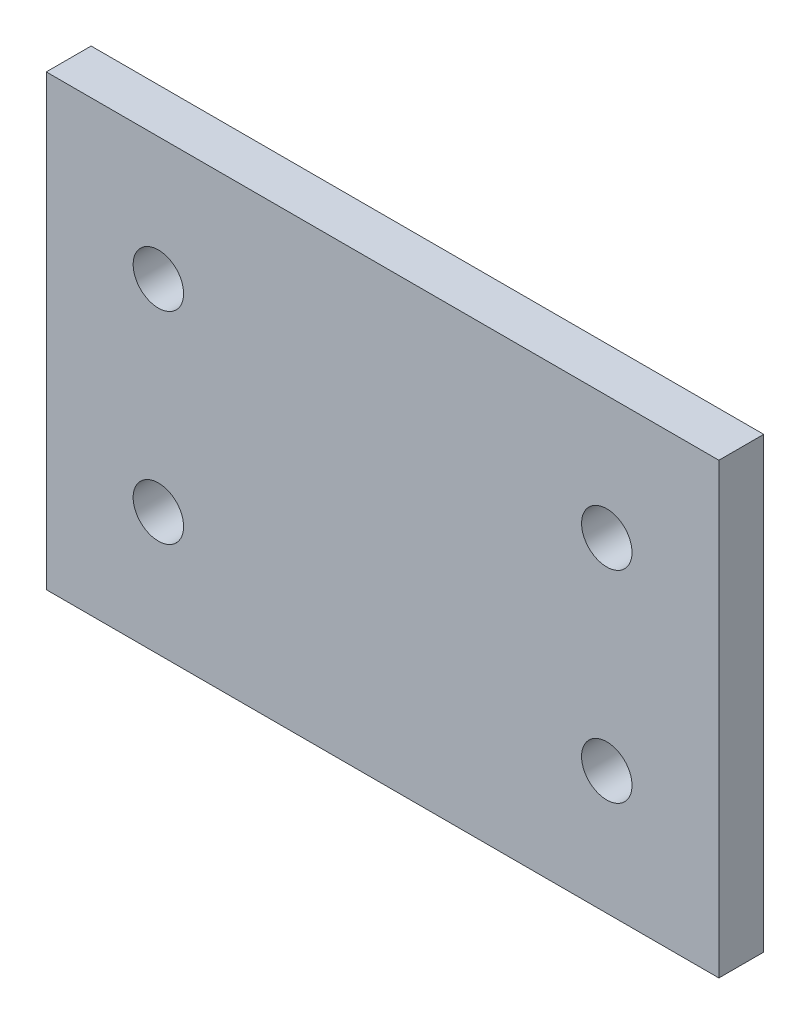
SolidWorks part; units mm, degrees
material "SKD11淬火HRC56-60"
ref_plane "前基準面" through (0, 0, 0) normal (0, 0, 1) x (1, 0, 0)
ref_plane "上基準面" through (0, 0, 0) normal (0, 1, 0) x (1, 0, 0)
ref_plane "右基準面" through (0, 0, 0) normal (1, 0, 0) x (0, 0, -1)
sketch "草图1" plane through (0, 0, 0) normal (0, 0, 1) x (1, 0, 0)
  line L1 (0, 0) -> (60, 0)
  line L2 (0, 0) -> (0, 40)
  line L3 (0, 40) -> (60, 40)
  line L4 (60, 0) -> (60, 40)
  dimension "D1" = 60
  dimension "D2" = 40
extrude "凸台-拉伸1" add sketch "草图1" along normal blind 4
sketch "草图2" plane through (0, 0, 4) normal (0, 0, 1) x (1, 0, 0)
  line L0 (0, 20) -> (60, 20) construction
  line L1 (0, 40) -> (0, 0) construction
  line L2 (60, 0) -> (60, 40) construction
  line L3 (30, 0) -> (30, 35.731) construction
  line L4 (0, 0) -> (60, 0) construction
  circle A0 centre (10, 11) radius 2.25
  circle A1 centre (50, 11) radius 2.25
  circle A2 centre (50, 29) radius 2.25
  circle A3 centre (10, 29) radius 2.25
  dimension "D1" = 4.5
  dimension "D2" = 18
  dimension "D3" = 40
extrude "切除-拉伸1" cut sketch "草图2" against normal through all
